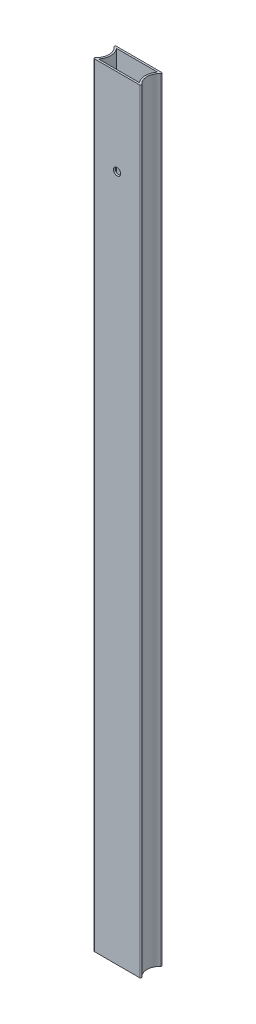
SolidWorks part; units mm, degrees
ref_plane "Front Plane" through (0, 0, 0) normal (0, 0, 1) x (1, 0, 0)
ref_plane "Top Plane" through (0, 0, 0) normal (0, 1, 0) x (1, 0, 0)
ref_plane "Right Plane" through (0, 0, 0) normal (1, 0, 0) x (0, 0, -1)
sketch "Sketch1" plane through (0, 0, 0) normal (0, 1, 0) x (1, 0, 0)
  line L0 (-35, 0) -> (35, 0) construction
  line L1 (-24.802, -12) -> (24.802, -12)
  line L2 (-27.7889, -12) -> (-27.7889, 12) construction
  line L3 (-24.802, 12) -> (24.802, 12)
  line L4 (27.7889, -12) -> (27.7889, 12) construction
  line L5 (-27.7889, -12) -> (27.7889, 12) construction
  line L6 (-27.7889, 12) -> (27.7889, -12) construction
  arc A0 (-25.4818, 10.2667) -> (-25.4818, -10.2667) centre (-35, 0) cw
  arc A1 (25.4818, -10.2667) -> (25.4818, 10.2667) centre (35, 0) cw
  arc A2 (-24.802, 12) -> (-25.4818, 10.2667) centre (-24.802, 11) ccw
  arc A3 (-25.4818, -10.2667) -> (-24.802, -12) centre (-24.802, -11) ccw
  arc A4 (24.802, -12) -> (25.4818, -10.2667) centre (24.802, -11) ccw
  arc A5 (24.802, 12) -> (25.4818, 10.2667) centre (24.802, 11) cw
  point P0 (0, 0)
  dimension "D3" = 14
  dimension "D4" = 1
  dimension "D1" = 24
  dimension "D2" = 70
extrude "Boss-Extrude1" add sketch "Sketch1" along normal blind 850
shell "Shell1" thickness 2
sketch "Sketch2" plane through (0, 0, -12) normal (0, 0, -1) x (-1, 0, 0)
  line L0 (0, 850) -> (0, 755) construction
  line L2 (-24.802, 850) -> (24.802, 850) construction
  circle A0 centre (0, 755) radius 4
  dimension "D2" = 8
  dimension "D1" = 95
extrude "Cut-Extrude1" cut sketch "Sketch2" against normal through all
